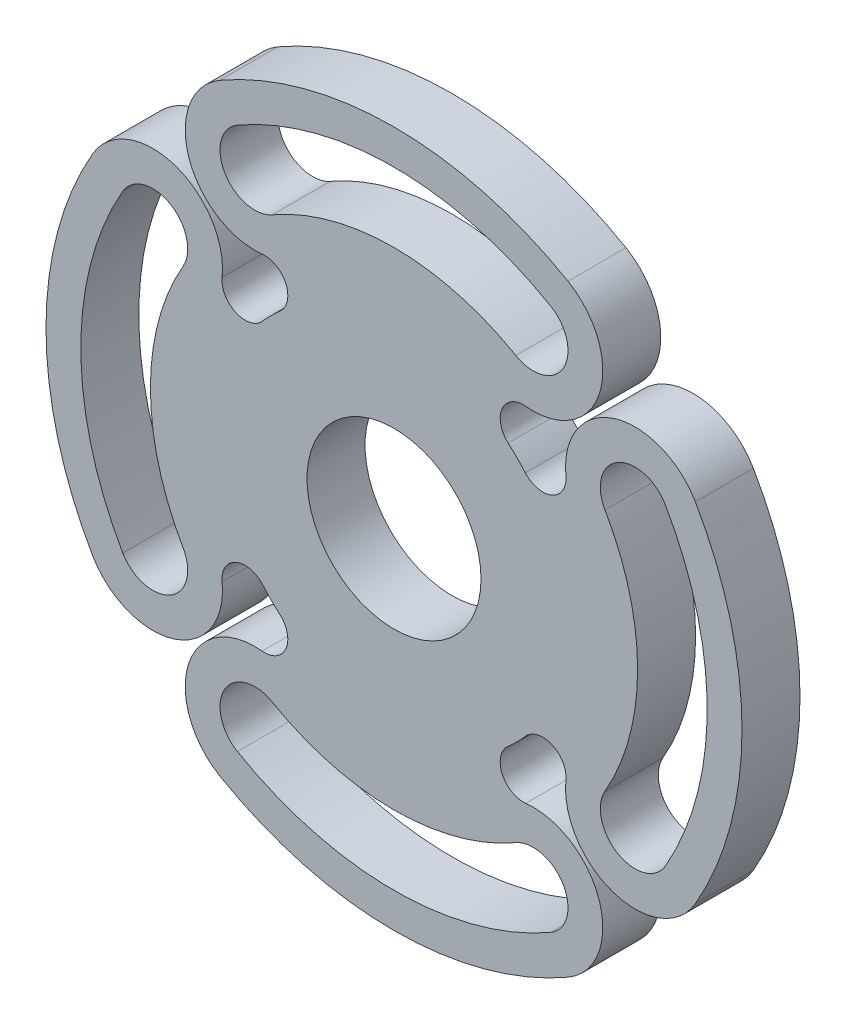
SolidWorks part; units mm, degrees
ref_plane "Front Plane" through (0, 0, 0) normal (0, 0, 1) x (1, 0, 0)
ref_plane "Top Plane" through (0, 0, 0) normal (0, 1, 0) x (1, 0, 0)
ref_plane "Right Plane" through (0, 0, 0) normal (1, 0, 0) x (0, 0, -1)
sketch "Sketch2" plane through (0, 0, 0) normal (0, 0, 1) x (1, 0, 0)
  line L0 (0, 0) -> (0, 74.6622) construction
  arc A0 (-19.6829, 22.6403) -> (-22.6403, 19.6829) centre (0, 0) ccw
  arc A1 (-24, 41.5692) -> (24, 41.5692) centre (0, 0) cw construction
  arc A2 (30, 51.9615) -> (-30, 51.9615) centre (0, 0) ccw
  arc A3 (18, 31.1769) -> (-18, 31.1769) centre (0, 0) ccw
  arc A4 (18, 31.1769) -> (30, 51.9615) centre (24, 41.5692) ccw
  arc A5 (-30, 51.9615) -> (-18, 31.1769) centre (-24, 41.5692) ccw
  arc A6 (24, 41.5692) -> (-24, 41.5692) centre (0, 0) ccw construction
  arc A7 (27, 46.7654) -> (-27, 46.7654) centre (0, 0) ccw
  arc A8 (21, 36.3731) -> (-21, 36.3731) centre (0, 0) ccw
  arc A9 (21, 36.3731) -> (27, 46.7654) centre (24, 41.5692) ccw
  arc A10 (-27, 46.7654) -> (-21, 36.3731) centre (-24, 41.5692) ccw
  arc A11 (-22.7305, 29.6366) -> (-19.6829, 22.6403) centre (-22.3073, 25.659) cw
  arc A12 (22.7305, 29.6366) -> (19.6829, 22.6403) centre (22.3073, 25.659) ccw
  arc A13 (31.1769, -18) -> (31.1769, 18) centre (0, 0) ccw
  arc A14 (31.1769, -18) -> (51.9615, -30) centre (41.5692, -24) ccw
  arc A15 (51.9615, 30) -> (31.1769, 18) centre (41.5692, 24) ccw
  arc A16 (51.9615, -30) -> (51.9615, 30) centre (0, 0) ccw
  arc A17 (29.6366, 22.7305) -> (22.6403, 19.6829) centre (25.659, 22.3073) cw
  arc A18 (29.6366, -22.7305) -> (22.6403, -19.6829) centre (25.659, -22.3073) ccw
  arc A19 (41.5692, 24) -> (41.5692, -24) centre (0, 0) cw construction
  arc A20 (41.5692, -24) -> (41.5692, 24) centre (0, 0) ccw construction
  arc A21 (46.7654, -27) -> (46.7654, 27) centre (0, 0) ccw
  arc A22 (36.3731, -21) -> (36.3731, 21) centre (0, 0) ccw
  arc A23 (36.3731, -21) -> (46.7654, -27) centre (41.5692, -24) ccw
  arc A24 (46.7654, 27) -> (36.3731, 21) centre (41.5692, 24) ccw
  arc A25 (-18, -31.1769) -> (18, -31.1769) centre (0, 0) ccw
  arc A26 (-18, -31.1769) -> (-30, -51.9615) centre (-24, -41.5692) ccw
  arc A27 (30, -51.9615) -> (18, -31.1769) centre (24, -41.5692) ccw
  arc A28 (-30, -51.9615) -> (30, -51.9615) centre (0, 0) ccw
  arc A29 (22.7305, -29.6366) -> (19.6829, -22.6403) centre (22.3073, -25.659) cw
  arc A30 (-22.7305, -29.6366) -> (-19.6829, -22.6403) centre (-22.3073, -25.659) ccw
  arc A31 (24, -41.5692) -> (-24, -41.5692) centre (0, 0) cw construction
  arc A32 (-24, -41.5692) -> (24, -41.5692) centre (0, 0) ccw construction
  arc A33 (-27, -46.7654) -> (27, -46.7654) centre (0, 0) ccw
  arc A34 (-21, -36.3731) -> (21, -36.3731) centre (0, 0) ccw
  arc A35 (-21, -36.3731) -> (-27, -46.7654) centre (-24, -41.5692) ccw
  arc A36 (27, -46.7654) -> (21, -36.3731) centre (24, -41.5692) ccw
  arc A37 (-31.1769, 18) -> (-31.1769, -18) centre (0, 0) ccw
  arc A38 (-31.1769, 18) -> (-51.9615, 30) centre (-41.5692, 24) ccw
  arc A39 (-51.9615, -30) -> (-31.1769, -18) centre (-41.5692, -24) ccw
  arc A40 (-51.9615, 30) -> (-51.9615, -30) centre (0, 0) ccw
  arc A41 (-29.6366, -22.7305) -> (-22.6403, -19.6829) centre (-25.659, -22.3073) cw
  arc A42 (-29.6366, 22.7305) -> (-22.6403, 19.6829) centre (-25.659, 22.3073) ccw
  arc A43 (-41.5692, -24) -> (-41.5692, 24) centre (0, 0) cw construction
  arc A44 (-41.5692, 24) -> (-41.5692, -24) centre (0, 0) ccw construction
  arc A45 (-46.7654, 27) -> (-46.7654, -27) centre (0, 0) ccw
  arc A46 (-36.3731, 21) -> (-36.3731, -21) centre (0, 0) ccw
  arc A47 (-36.3731, 21) -> (-46.7654, 27) centre (-41.5692, 24) ccw
  arc A48 (-46.7654, -27) -> (-36.3731, -21) centre (-41.5692, -24) ccw
  arc A49 (22.6403, 19.6829) -> (19.6829, 22.6403) centre (0, 0) ccw
  arc A50 (19.6829, -22.6403) -> (22.6403, -19.6829) centre (0, 0) ccw
  arc A51 (-22.6403, -19.6829) -> (-19.6829, -22.6403) centre (0, 0) ccw
  circle A52 centre (0, 0) radius 15
  point P5 (0, 48)
  point P11 (0, 48)
  point P31 (48, 0)
  point P36 (48, 0)
  point P51 (0, -48)
  point P56 (0, -48)
  point P71 (-48, 0)
  point P76 (-48, 0)
  point P89 (0, 0)
  dimension "D1" = 60
  dimension "D2" = 48
  dimension "D4" = 60
  dimension "D5" = 30
  dimension "D6" = 54
  dimension "D7" = 4
  dimension "D8" = 30
  dimension "D3" = 30
extrude "Boss-Extrude1" add sketch "Sketch2" along normal mid plane 10 contours A41 A51 A30 A26 A25 A27 A29 A50 A18 A14 A13 A15 A17 A49 A12 A4 A3 A5 A11 A0 A42 A38 A37 A39 | A38 A40 A39 A37 A48 A45 A47 A46 | A2 A5 A3 A4 A10 A7 A9 A8 | A14 A16 A15 A13 A24 A21 A23 A22 | A26 A28 A27 A25 A36 A33 A35 A34
